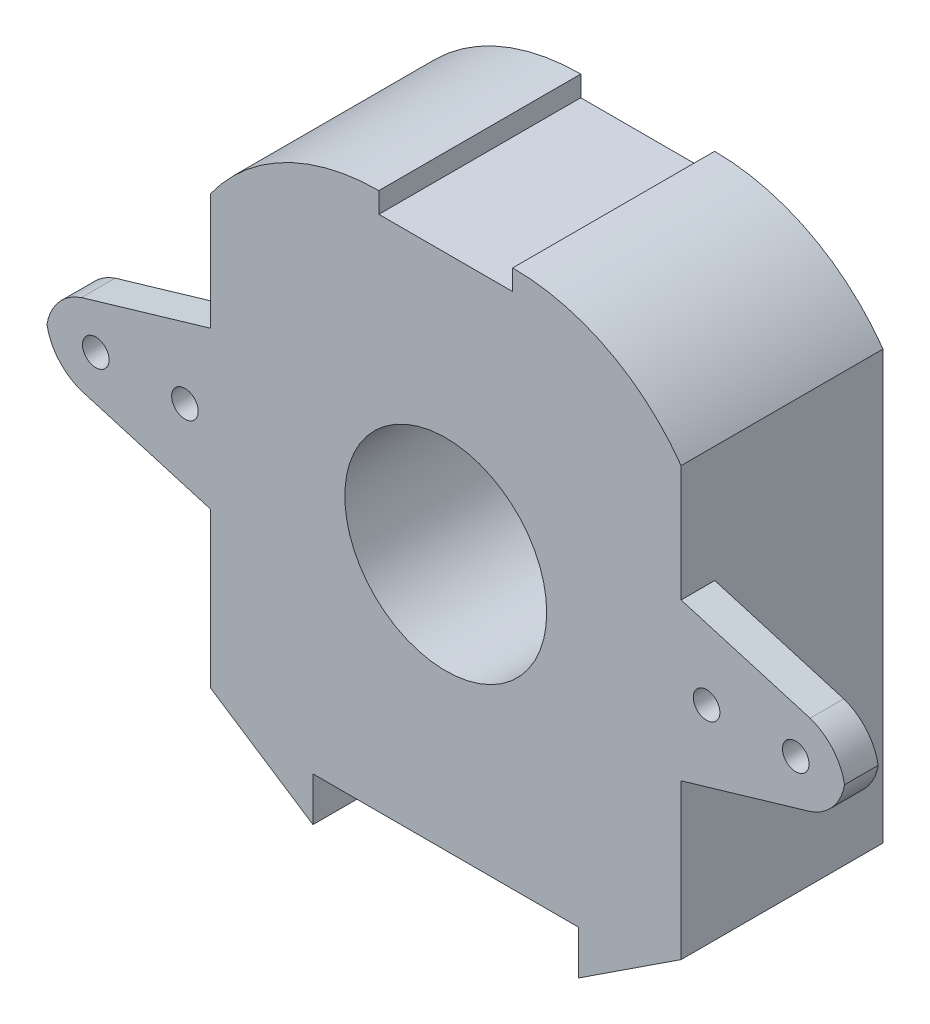
SolidWorks part; units mm, degrees
ref_plane "Front Plane" through (0, 0, 0) normal (0, 0, 1) x (1, 0, 0)
ref_plane "Top Plane" through (0, 0, 0) normal (0, 1, 0) x (1, 0, 0)
ref_plane "Right Plane" through (0, 0, 0) normal (1, 0, 0) x (0, 0, -1)
sketch "Sketch1" plane through (0, 0, 0) normal (0, 0, 1) x (1, 0, 0)
  line L0 (0, 70.9446) -> (0, 19.6997) construction
  line L2 (-17.7635, 14.683) -> (-17.7635, -17.609)
  line L3 (-17.7635, -17.609) -> (-10.0241, -22.6796)
  line L4 (-10.0241, -22.6796) -> (-10.0241, -19.3595)
  line L5 (-10.0241, -19.3595) -> (10.0241, -19.3595)
  line L6 (-5.0511, 21.2507) -> (-5.0511, 19.6997)
  line L7 (-5.0511, 19.6997) -> (5.0511, 19.6997)
  line L8 (10.0241, -22.6796) -> (10.0241, -19.3595)
  line L9 (17.7635, -17.609) -> (10.0241, -22.6796)
  line L10 (17.7635, 14.683) -> (17.7635, -17.609)
  line L11 (5.0511, 21.2507) -> (5.0511, 19.6997)
  line L13 (0, 19.6997) -> (0, -83.3132) construction
  arc A0 (-5.0511, 21.2507) -> (-17.7635, 14.683) centre (-5.0511, 5.6637) ccw
  arc A1 (5.0511, 21.2507) -> (17.7635, 14.683) centre (5.0511, 5.6637) cw
  point P17 (0, -19.3595)
  point P21 (0, 19.6997)
  point P24 (0, 0)
extrude "Boss-Extrude2" add sketch "Sketch1" along normal blind 15.24
sketch "Sketch5" plane through (0, 0, 15.24) normal (0, 0, 1) x (1, 0, 0)
  circle A0 centre (0, 0) radius 7.62
  dimension "D1" = 15.24
extrude "Cut-Extrude2" cut sketch "Sketch5" against normal blind 15.24
sketch "Sketch6" plane through (0, 0, 15.24) normal (0, 0, 1) x (1, 0, 0)
  line L2 (-27.4971, 3.0373) -> (-17.7635, 5.9001)
  line L3 (-17.7635, 14.683) -> (-17.7635, -17.609) construction
  line L4 (-17.7635, 5.9001) -> (-17.7635, -5.921)
  line L5 (-27.4971, -3.0582) -> (-17.7635, -5.921)
  line L6 (0, 24.5613) -> (0, -29.2199) construction
  line L7 (27.4971, 3.0373) -> (17.7635, 5.9001)
  line L8 (27.4971, -3.0582) -> (17.7635, -5.921)
  line L9 (17.7635, 5.9001) -> (17.7635, -5.921)
  arc A0 (-27.4971, 3.0373) -> (-30.1001, -0.0104) centre (-26.2297, -0.6805) ccw
  arc A1 (-27.4971, -3.0582) -> (-30.1001, -0.0104) centre (-26.2297, 0.6596) cw
  arc A2 (27.4971, 3.0373) -> (30.1001, -0.0104) centre (26.2297, -0.6805) cw
  arc A3 (27.4971, -3.0582) -> (30.1001, -0.0104) centre (26.2297, 0.6596) ccw
  point P3 (-19.5103, 9.4005)
extrude "Boss-Extrude3" add sketch "Sketch6" against normal blind 2.54
sketch "Sketch7" plane through (0, 0, 0) normal (0, 0, -1) x (-1, 0, 0)
  line L0 (-34.7295, 0) -> (42.0609, 0) construction
  line L1 (0, 25.6042) -> (0, -30.1557) construction
  circle A0 centre (-19.685, 0) radius 1.0033
  circle A1 centre (-26.416, 0) radius 1.0033
  circle A2 centre (19.685, 0) radius 1.0033
  circle A3 centre (26.416, 0) radius 1.0033
  dimension "D1" = 2.0066
  dimension "D2" = 2.0066
  dimension "D3" = 39.37
  dimension "D4" = 52.832
extrude "Cut-Extrude5" cut sketch "Sketch7" along normal through all both and the other way through all
